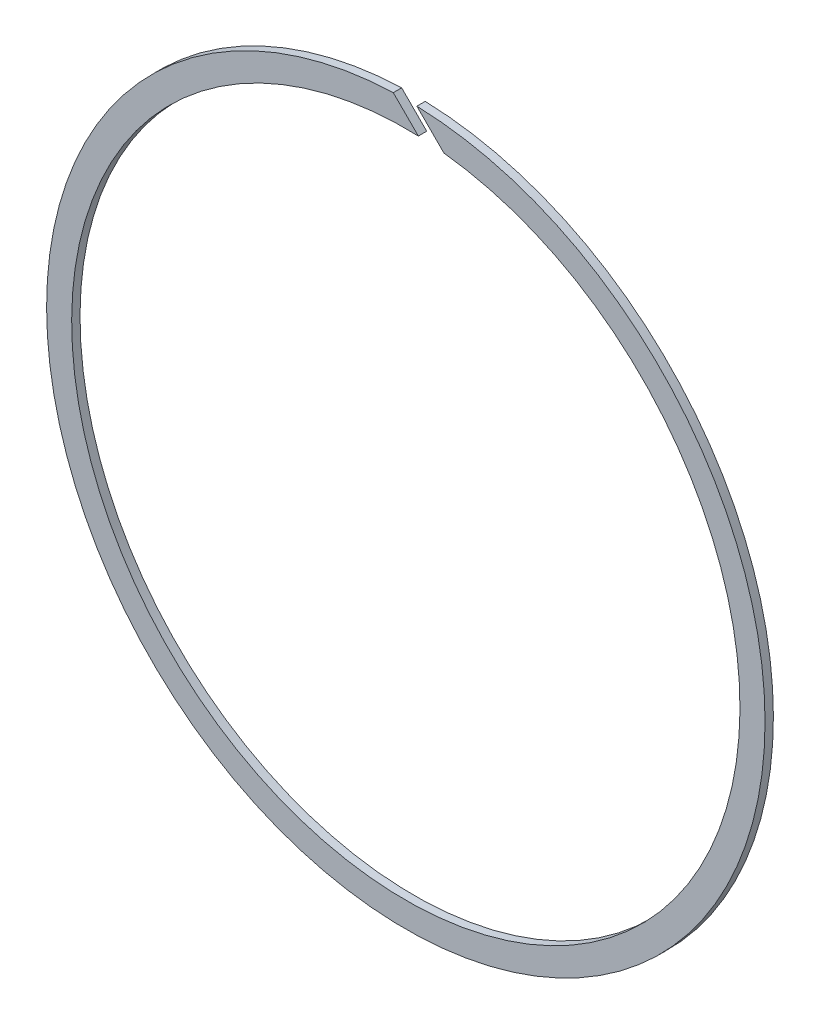
SolidWorks part; units mm, degrees
material "AISI 316 Stainless Steel Sheet (SS)"
ref_plane "Front Plane" through (0, 0, 0) normal (0, 0, 1) x (1, 0, 0)
ref_plane "Top Plane" through (0, 0, 0) normal (0, 1, 0) x (1, 0, 0)
ref_plane "Right Plane" through (0, 0, 0) normal (1, 0, 0) x (0, 0, -1)
sketch "Sketch1" plane through (0, 0, 0) normal (0, 0, 1) x (1, 0, 0)
  line L0 (0, 0) -> (0, 20.7364) construction
  line L1 (-0.7505, 21.4869) -> (0.7505, 19.9859) construction
  line L2 (0.6608, 21.4898) -> (2.2811, 19.8695)
  line L3 (-0.7505, 21.4869) -> (0.7505, 19.9859)
  arc A0 (-0.7505, 21.4869) -> (0.6608, 21.4898) centre (0, 0) ccw
  arc A1 (0.7505, 19.9859) -> (2.2811, 19.8695) centre (0, 0) ccw
  point P7 (0, 20.7364)
  dimension "D1" = 40
  dimension "D2" = 43
  dimension "D3" = 45
  dimension "D4" = 1
extrude "Boss-Extrude1" add sketch "Sketch1" along normal mid plane 0.5
